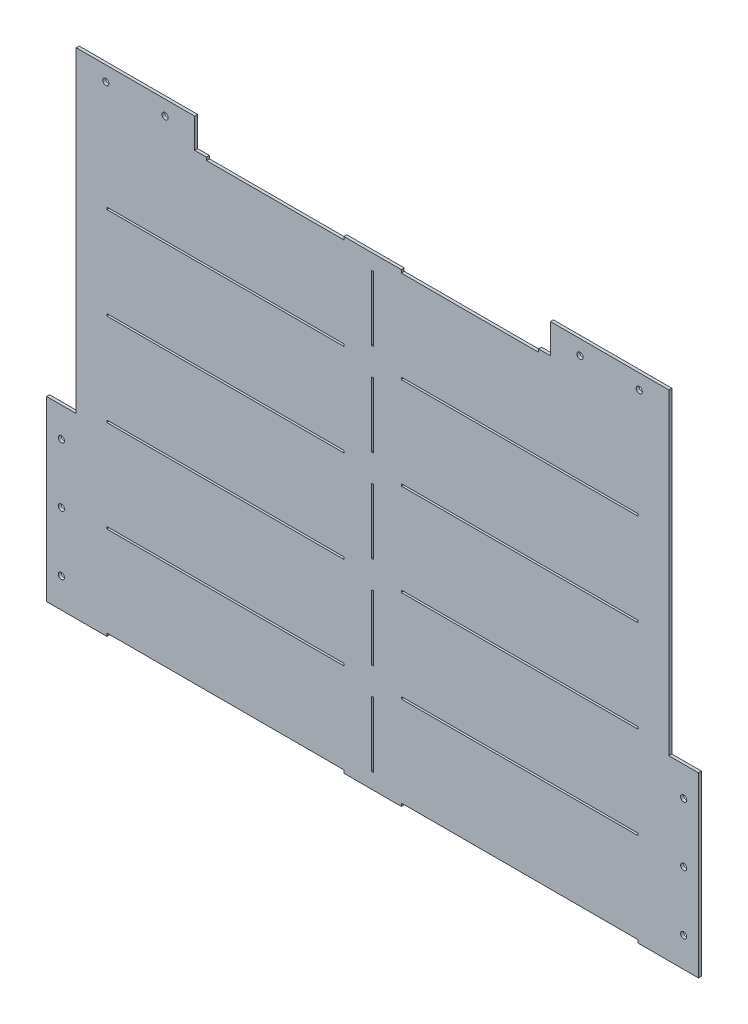
SolidWorks part; units mm, degrees
material "6061-T6 (SS)"
ref_plane "X-Y Datum" through (0, 0, 0) normal (0, 0, 1) x (1, 0, 0)
ref_plane "X-Z Datum" through (0, 0, 0) normal (0, 1, 0) x (1, 0, 0)
ref_plane "Y-Z Datum" through (0, 0, 0) normal (1, 0, 0) x (0, 0, -1)
sketch "Master Sketch" plane through (0, 0, 0) normal (0, 0, 1) x (1, 0, 0)
  line L0 (1.143, 50.5714) -> (314.5028, 50.5714) construction
  line L1 (-317.6778, 249.174) -> (317.6778, 249.174)
  line L2 (-317.6778, 249.174) -> (-317.6778, -249.174)
  line L3 (-317.6778, -249.174) -> (317.6778, -249.174)
  line L4 (317.6778, 249.174) -> (317.6778, -249.174)
  line L5 (-317.6778, 249.174) -> (317.6778, -249.174) construction
  line L6 (-317.6778, -249.174) -> (317.6778, 249.174) construction
  line L7 (-1.143, 249.174) -> (1.143, 249.174) construction
  line L8 (-1.143, 249.174) -> (-1.143, -249.174) construction
  line L9 (-1.143, -249.174) -> (1.143, -249.174) construction
  line L10 (1.143, 249.174) -> (1.143, -249.174) construction
  line L11 (-1.143, 249.174) -> (1.143, -249.174) construction
  line L12 (-1.143, -249.174) -> (1.143, 249.174) construction
  line L13 (1.143, 245.999) -> (314.5028, 245.999) construction
  line L14 (1.143, 245.999) -> (1.143, 149.4282) construction
  line L15 (1.143, 149.4282) -> (314.5028, 149.4282) construction
  line L16 (314.5028, 245.999) -> (314.5028, 149.4282) construction
  line L17 (1.143, 245.999) -> (314.5028, 149.4282) construction
  line L18 (1.143, 149.4282) -> (314.5028, 245.999) construction
  line L19 (1.143, 147.1422) -> (314.5028, 147.1422) construction
  line L20 (314.5028, 147.1422) -> (314.5028, 50.5714) construction
  line L21 (1.143, 147.1422) -> (1.143, 50.5714) construction
  line L22 (1.143, -48.2854) -> (314.5028, -48.2854) construction
  line L23 (1.143, 48.2854) -> (314.5028, 48.2854) construction
  line L24 (314.5028, 48.2854) -> (314.5028, -48.2854) construction
  line L25 (1.143, 48.2854) -> (1.143, -48.2854) construction
  line L26 (1.143, -147.1422) -> (314.5028, -147.1422) construction
  line L27 (1.143, -50.5714) -> (314.5028, -50.5714) construction
  line L28 (314.5028, -50.5714) -> (314.5028, -147.1422) construction
  line L29 (1.143, -50.5714) -> (1.143, -147.1422) construction
  line L30 (1.143, -245.999) -> (314.5028, -245.999) construction
  line L31 (1.143, -149.4282) -> (314.5028, -149.4282) construction
  line L32 (314.5028, -149.4282) -> (314.5028, -245.999) construction
  line L33 (1.143, -149.4282) -> (1.143, -245.999) construction
  line L34 (0, 249.174) -> (0, -249.174) construction
  line L35 (-1.143, -149.4282) -> (-1.143, -245.999) construction
  line L36 (-314.5028, -149.4282) -> (-314.5028, -245.999) construction
  line L37 (-1.143, -149.4282) -> (-314.5028, -149.4282) construction
  line L38 (-1.143, -245.999) -> (-314.5028, -245.999) construction
  line L39 (-1.143, -50.5714) -> (-1.143, -147.1422) construction
  line L40 (-314.5028, -50.5714) -> (-314.5028, -147.1422) construction
  line L41 (-1.143, -50.5714) -> (-314.5028, -50.5714) construction
  line L42 (-1.143, -147.1422) -> (-314.5028, -147.1422) construction
  line L43 (-1.143, 48.2854) -> (-1.143, -48.2854) construction
  line L44 (-314.5028, 48.2854) -> (-314.5028, -48.2854) construction
  line L45 (-1.143, 48.2854) -> (-314.5028, 48.2854) construction
  line L46 (-1.143, -48.2854) -> (-314.5028, -48.2854) construction
  line L47 (-1.143, 147.1422) -> (-1.143, 50.5714) construction
  line L48 (-314.5028, 147.1422) -> (-314.5028, 50.5714) construction
  line L49 (-1.143, 147.1422) -> (-314.5028, 147.1422) construction
  line L50 (-1.143, 149.4282) -> (-314.5028, 245.999) construction
  line L51 (-1.143, 245.999) -> (-314.5028, 149.4282) construction
  line L52 (-314.5028, 245.999) -> (-314.5028, 149.4282) construction
  line L53 (-1.143, 149.4282) -> (-314.5028, 149.4282) construction
  line L54 (-1.143, 245.999) -> (-1.143, 149.4282) construction
  line L55 (-1.143, 245.999) -> (-314.5028, 245.999) construction
  line L56 (-1.143, 249.174) -> (-1.143, -249.174) construction
  line L57 (-1.143, 50.5714) -> (-314.5028, 50.5714) construction
  line L59 (2.413, -152.8699) -> (313.2328, -152.8699) construction
  line L60 (2.413, -152.8699) -> (2.413, -242.5573) construction
  line L61 (2.413, -242.5573) -> (313.2328, -242.5573) construction
  line L62 (313.2328, -152.8699) -> (313.2328, -242.5573) construction
  line L63 (2.413, -152.8699) -> (313.2328, -242.5573) construction
  line L64 (2.413, -242.5573) -> (313.2328, -152.8699) construction
  point P0 (0, 0)
  point P6 (0, 0)
  point P11 (157.8229, 197.7136)
  point P54 (-157.8229, 197.7136)
  point P55 (157.8229, -197.7136)
  point P60 (157.8229, -149.4282)
  point P61 (314.5028, -197.7136)
  point P62 (-314.5028, 98.8568)
  point P63 (-314.5028, 0)
  dimension "D1" = 3.175
  dimension "D2" = 498.348
  dimension "D3" = 2.286
  dimension "D4" = 313.3598
  dimension "D5" = 96.5708
  dimension "D6" = 3.175
  dimension "D7" = 5
  dimension "D8" = 2.286
  dimension "D9" = 89.6874
  dimension "D10" = 310.8198
  dimension "D11" = 98.8568
  dimension "D12" = 635.3556
extrude "Boss-Extrude1" add sketch "Master Sketch" along normal blind 3.175
sketch "Sketch2" plane through (0, 0, 3.175) normal (0, 0, 1) x (1, 0, 0)
  line L0 (0, 317.2302) -> (0, -317.2302) construction
  line L7 (-380.7135, 0) -> (380.7135, 0) construction
  line L9 (-333.5528, -58.674) -> (-333.5528, -249.174) construction
  line L10 (-317.6778, -249.174) -> (-349.4278, -249.174)
  line L11 (-317.6778, -249.174) -> (-317.6778, -58.674)
  line L12 (-317.6778, -58.674) -> (-349.4278, -58.674)
  line L13 (-349.4278, -249.174) -> (-349.4278, -58.674)
  circle A7 centre (-333.5528, -153.924) radius 3 construction
  circle A10 centre (-333.5528, -90.424) radius 3 construction
  circle A11 centre (-333.5528, -153.924) radius 3 construction
  circle A12 centre (-333.5528, -217.424) radius 3 construction
  point P4 (0, 0)
  point P18 (0, 0)
  dimension "D8" = 31.75
  dimension "D10" = 6
  dimension "D9" = 190.5
  dimension "D13" = 63.5
  dimension "D14" = 63.5
  dimension "D11" = 2
  dimension "D12" = 2
extrude "Boss-Extrude2" add sketch "Sketch2" against normal blind 3.175
hole_wizard "M6 Clearance Hole1" positions "Sketch3" profile "Sketch4" hole size "M6" standard "ANSI Metric" end condition through all
sketch "Sketch3" plane through (0, 0, 3.175) normal (0, 0, 1) x (1, 0, 0)
  point P34 (-333.5528, -90.424)
  point P37 (-333.5528, -153.924)
  point P40 (-333.5528, -217.424)
sketch "Sketch4" plane through (-333.5528, -90.424, 3.175) normal (1, 0, 0) x (0, -1, 0)
  line L0 (0, 0) -> (0, 3.175)
  line L1 (0, 3.175) -> (3.3, 3.175)
  line L2 (3.3, 3.175) -> (3.3, 0)
  line L5 (3.3, 0) -> (0, 0)
  line L11 (0, -6.35) -> (0, 107.95) construction
  dimension "Thru Hole Dia." = 6.6
  dimension "Thru Hole Depth" = 3.175
mirror "Mirror1" about plane through (0, 0, 0) normal (1, 0, 0) of "Boss-Extrude2", "M6 Clearance Hole1"
sketch "Sketch5" plane through (0, 0, 3.175) normal (0, 0, 1) x (1, 0, 0)
  line L5 (-1.143, 232.6386) -> (1.143, 232.6386)
  line L6 (-1.143, 232.6386) -> (-1.143, 162.7886)
  line L7 (-1.143, 162.7886) -> (1.143, 162.7886)
  line L8 (1.143, 232.6386) -> (1.143, 162.7886)
  line L9 (-157.8229, 197.7136) -> (157.8229, 197.7136) construction
  line L10 (-1.143, 232.6386) -> (1.143, 162.7886) construction
  line L11 (-1.143, 162.7886) -> (1.143, 232.6386) construction
  point P0 (0, 0)
  point P1 (0, 197.7136)
  dimension "D1" = 2.286
  dimension "D2" = 69.85
extrude "Cut-Extrude1" cut sketch "Sketch5" against normal through all
pattern_linear "LPattern1" count 5 spacing 98.8568 along (0, -1, 0) of "Cut-Extrude1"
sketch "Sketch7" plane through (0, 0, 3.175) normal (0, 0, 1) x (1, 0, 0)
  line L0 (-157.8229, 149.4282) -> (-157.8229, 147.1422) construction
  line L1 (-1.143, 149.4282) -> (-314.5028, 149.4282) construction
  line L2 (-1.143, 147.1422) -> (-314.5028, 147.1422) construction
  line L3 (-157.8229, 50.5714) -> (-157.8229, 48.2854) construction
  line L4 (-284.8229, 149.4282) -> (-30.8229, 149.4282)
  line L5 (-284.8229, 149.4282) -> (-284.8229, 147.1422)
  line L6 (-284.8229, 147.1422) -> (-30.8229, 147.1422)
  line L7 (-30.8229, 149.4282) -> (-30.8229, 147.1422)
  line L8 (-284.8229, 149.4282) -> (-30.8229, 147.1422) construction
  line L9 (-284.8229, 147.1422) -> (-30.8229, 149.4282) construction
  line L10 (-1.143, 50.5714) -> (-314.5028, 50.5714) construction
  line L11 (-1.143, 48.2854) -> (-314.5028, 48.2854) construction
  point P6 (-157.8229, 148.2852)
  dimension "D1" = 2.286
  dimension "D2" = 254
extrude "Cut-Extrude3" cut sketch "Sketch7" against normal through all
pattern_linear "LPattern2" count 4 spacing 98.8568 along (0, -1, 0) of "Cut-Extrude3"
mirror "Mirror4" about plane through (0, 0, 0) normal (1, 0, 0) of "LPattern2", "Cut-Extrude3"
sketch "Sketch10" plane through (0, 0, 3.175) normal (0, 0, 1) x (1, 0, 0)
  line L8 (-317.6778, 265.049) -> (-190.6778, 265.049) construction
  line L9 (-317.6778, 249.174) -> (-190.6778, 249.174)
  line L10 (-317.6778, 249.174) -> (-317.6778, 280.924)
  line L11 (-317.6778, 280.924) -> (-190.6778, 280.924)
  line L12 (-190.6778, 249.174) -> (-190.6778, 280.924)
  line L13 (-254.1778, 280.924) -> (-254.1778, 249.174) construction
  line L14 (-254.1778, 265.049) -> (-317.6778, 265.049) construction
  line L15 (-317.6778, 265.049) -> (-285.9278, 265.049) construction
  line L16 (-285.9278, 265.049) -> (-285.9278, 273.0891) construction
  circle A2 centre (-285.9278, 265.049) radius 3 construction
  circle A3 centre (-222.4278, 265.049) radius 3 construction
  dimension "D6" = 6
  dimension "D1" = 63.5
  dimension "D2" = 63.5
  dimension "D4" = 31.75
  dimension "D5" = 127
extrude "Boss-Extrude3" add sketch "Sketch10" against normal blind 3.175
hole_wizard "M6 Clearance Hole2" positions "Sketch11" profile "Sketch12" hole size "M6" standard "ANSI Metric" end condition through all
sketch "Sketch11" plane through (0, 0, 3.175) normal (0, 0, 1) x (1, 0, 0)
  point P7 (-285.9278, 265.049)
  point P10 (-222.4278, 265.049)
sketch "Sketch12" plane through (-285.9278, 265.049, 3.175) normal (1, 0, 0) x (0, -1, 0)
  line L0 (0, 0) -> (0, 3.175)
  line L1 (0, 3.175) -> (3.3, 3.175)
  line L2 (3.3, 3.175) -> (3.3, 0)
  line L5 (3.3, 0) -> (0, 0)
  line L11 (0, -6.35) -> (0, 107.95) construction
  dimension "Thru Hole Dia." = 6.6
  dimension "Thru Hole Depth" = 3.175
mirror "Mirror6" about plane through (0, 0, 0) normal (1, 0, 0) of "M6 Clearance Hole2", "Boss-Extrude3"
sketch "Sketch6" plane through (0, 0, 3.175) normal (0, 0, 1) x (1, 0, 0)
  line L0 (-157.8229, 245.999) -> (-157.8229, 249.174) construction
  line L1 (-1.143, 245.999) -> (-314.5028, 245.999) construction
  line L2 (-317.6778, 249.174) -> (317.6778, 249.174) construction
  line L3 (0, -78.309) -> (0, 78.309) construction
  line L4 (-284.8229, 249.174) -> (-30.8229, 249.174)
  line L5 (-284.8229, 249.174) -> (-284.8229, 245.999)
  line L6 (-284.8229, 245.999) -> (-30.8229, 245.999)
  line L7 (-30.8229, 249.174) -> (-30.8229, 245.999)
  line L8 (-284.8229, 249.174) -> (-30.8229, 245.999) construction
  line L9 (-284.8229, 245.999) -> (-30.8229, 249.174) construction
  line L10 (30.8229, 249.174) -> (30.8229, 245.999)
  line L11 (284.8229, 249.174) -> (30.8229, 249.174)
  line L12 (284.8229, 245.999) -> (30.8229, 245.999)
  line L13 (284.8229, 249.174) -> (284.8229, 245.999)
  line L14 (1.7463, 0) -> (-1.7463, 0) construction
  line L15 (-284.8229, -245.999) -> (-30.8229, -249.174) construction
  line L16 (-284.8229, -249.174) -> (-30.8229, -245.999) construction
  line L17 (-157.8229, -245.999) -> (-157.8229, -249.174) construction
  line L18 (284.8229, -249.174) -> (284.8229, -245.999)
  line L19 (284.8229, -245.999) -> (30.8229, -245.999)
  line L20 (284.8229, -249.174) -> (30.8229, -249.174)
  line L21 (30.8229, -249.174) -> (30.8229, -245.999)
  line L22 (-30.8229, -249.174) -> (-30.8229, -245.999)
  line L23 (-284.8229, -245.999) -> (-30.8229, -245.999)
  line L24 (-284.8229, -249.174) -> (-284.8229, -245.999)
  line L25 (-284.8229, -249.174) -> (-30.8229, -249.174)
  line L26 (-177.9778, 245.999) -> (-177.9778, 249.174)
  line L27 (-190.6778, 249.174) -> (-190.6778, 280.924) construction
  line L28 (177.9778, 245.999) -> (177.9778, 249.174)
  point P6 (-157.8229, 247.5865)
  point P29 (-157.8229, -247.5865)
  dimension "D1" = 3.175
  dimension "D2" = 254
  dimension "D3" = 12.7
extrude "Cut-Extrude2" cut sketch "Sketch6" against normal through all
